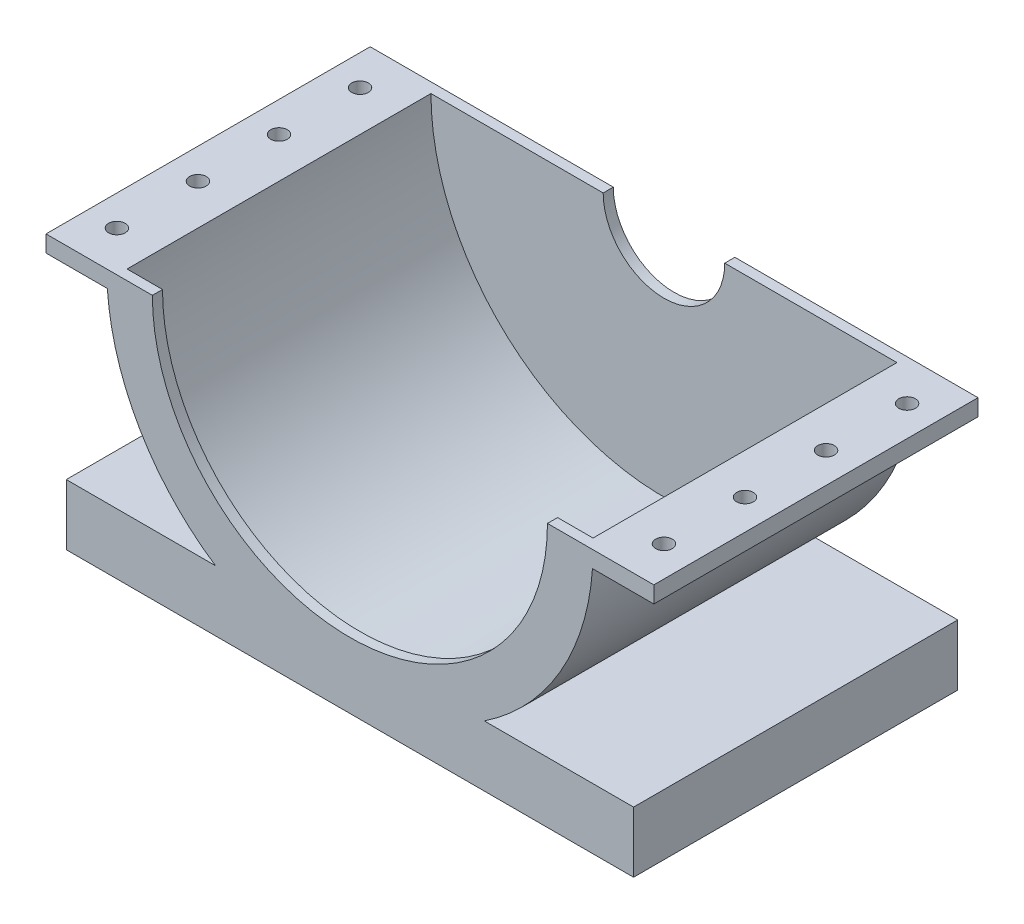
SolidWorks part; units mm, degrees
ref_plane "Front Plane" through (0, 0, 0) normal (0, 0, 1) x (1, 0, 0)
ref_plane "Top Plane" through (0, 0, 0) normal (0, 1, 0) x (1, 0, 0)
ref_plane "Right Plane" through (0, 0, 0) normal (1, 0, 0) x (0, 0, -1)
sketch "Sketch2" plane through (0, 0, 0) normal (0, 0, 1) x (1, 0, 0)
  line L0 (0, 146.05) -> (0, -19.05) construction
  line L2 (-177.8, 19.05) -> (-177.8, -19.05)
  line L3 (-177.8, -19.05) -> (177.8, -19.05)
  line L4 (177.8, 19.05) -> (177.8, -19.05)
  line L5 (-177.8, 19.05) -> (177.8, -19.05) construction
  line L6 (-177.8, -19.05) -> (177.8, 19.05) construction
  line L7 (-84.2423, 19.05) -> (-177.8, 19.05)
  line L8 (177.8, 19.05) -> (84.2423, 19.05)
  line L9 (-152.4, 146.05) -> (152.4, 146.05)
  line L10 (-152.4, 146.05) -> (-190.5, 146.05)
  line L11 (-190.5, 146.05) -> (-190.5, 135.636)
  line L12 (-190.5, 135.636) -> (-152.0438, 135.636)
  line L13 (190.5, 146.05) -> (152.4, 146.05)
  line L14 (190.5, 146.05) -> (190.5, 135.636)
  line L15 (190.5, 135.636) -> (152.0438, 135.636)
  arc A1 (-152.0438, 135.636) -> (152.0438, 135.636) centre (0, 146.05) ccw
  point P0 (0, 0)
  point P20 (0, 0)
  dimension "D4" = 152.4
  dimension "D1" = 38.1
  dimension "D2" = 355.6
  dimension "D3" = 165.1
  dimension "D5" = 38.1
  dimension "D6" = 38.1
  dimension "D7" = 10.414
  dimension "D8" = 10.414
extrude "Boss-Extrude1" add sketch "Sketch2" along normal mid plane 203.2 contours L12 A1 L15 L14 L13 L9 L10 L11 | A1 L7 L2 L3 L4 L8
sketch "Sketch4" plane through (0, 0, 0) normal (0, 0, 1) x (1, 0, 0)
  line L0 (190.5, 146.05) -> (-190.5, 146.05) construction
  line L1 (-146.05, 146.05) -> (146.05, 146.05)
  arc A0 (-146.05, 146.05) -> (146.05, 146.05) centre (0, 146.05) ccw
  dimension "D1" = 146.05
extrude "Cut-Extrude1" cut sketch "Sketch4" against normal mid plane 190.5
sketch "Sketch5" plane through (0, 0, 101.6) normal (0, 0, 1) x (1, 0, 0)
  line L0 (190.5, 146.05) -> (-190.5, 146.05) construction
  circle A0 centre (0, 146.05) radius 123.825
  dimension "D1" = 247.65
extrude "Cut-Extrude2" cut sketch "Sketch5" against normal up to next
sketch "Sketch6" plane through (0, 0, -95.25) normal (0, 0, 1) x (1, 0, 0)
  line L0 (146.05, 146.05) -> (-146.05, 146.05) construction
  circle A0 centre (0, 146.05) radius 38.1
  dimension "D1" = 76.2
extrude "Cut-Extrude3" cut sketch "Sketch6" against normal through all
sketch "Sketch7" plane through (0, 146.05, 0) normal (0, 1, 0) x (1, 0, 0)
  line L0 (-190.5, -101.6) -> (-190.5, 101.6) construction
  line L1 (-38.1, 101.6) -> (-190.5, 101.6) construction
  line L2 (0, -111.76) -> (0, 111.76) construction
  circle A0 centre (-171.45, 76.2) radius 5.207
  circle A1 centre (-171.45, 25.4) radius 5.207
  circle A2 centre (-171.45, -25.4) radius 5.207
  circle A3 centre (-171.45, -76.2) radius 5.207
  circle A5 centre (171.45, -76.2) radius 5.207
  circle A6 centre (171.45, -25.4) radius 5.207
  circle A7 centre (171.45, 25.4) radius 5.207
  circle A8 centre (171.45, 76.2) radius 5.207
  dimension "D1" = 10.414
  dimension "D2" = 19.05
  dimension "D3" = 25.4
  dimension "D4" = 4
extrude "Cut-Extrude4" cut sketch "Sketch7" against normal blind 83.566
